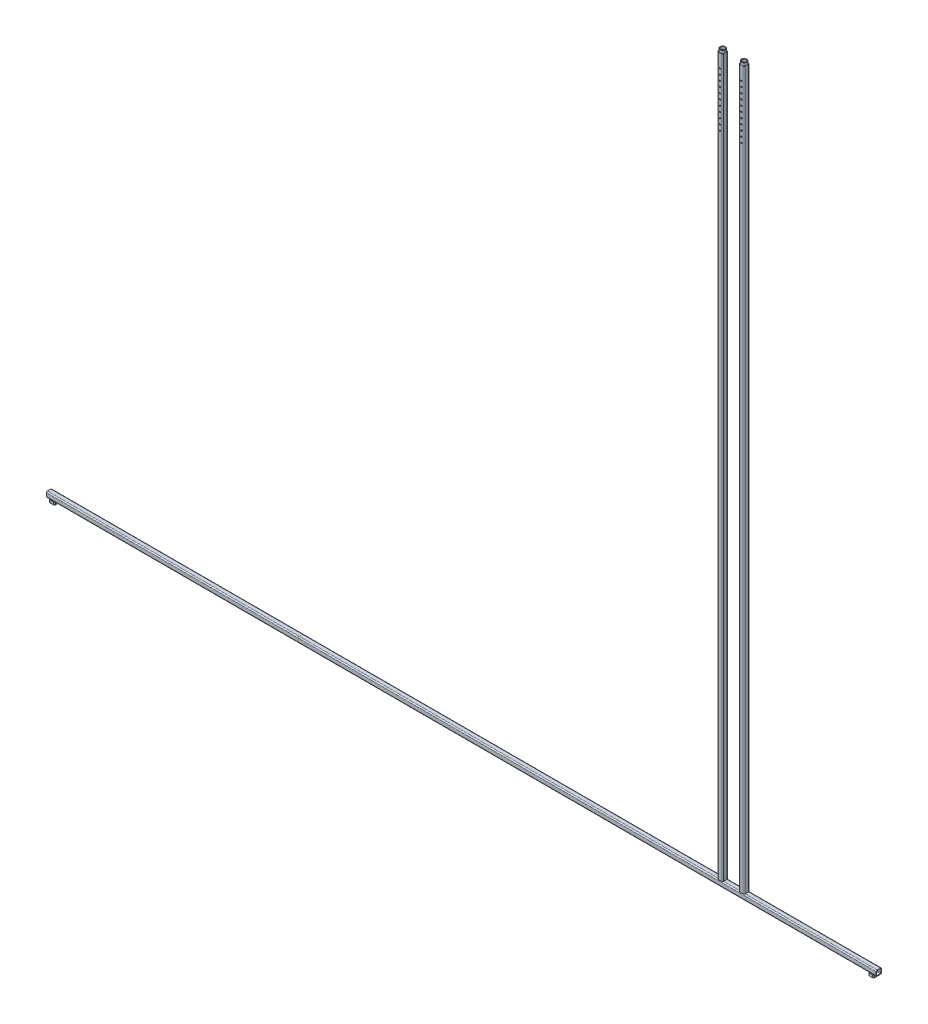
SolidWorks part; units mm, degrees
material "ASTM A36 Steel"
ref_plane "Front Plane" through (0, 0, 0) normal (0, 0, 1) x (1, 0, 0)
ref_plane "Top Plane" through (0, 0, 0) normal (0, 1, 0) x (1, 0, 0)
ref_plane "Right Plane" through (0, 0, 0) normal (1, 0, 0) x (0, 0, -1)
sketch "Sketch2" plane through (0, 0, 0) normal (0, 0, 1) x (1, 0, 0)
  line L0 (385.4461, 689.476) -> (385.4461, -1970.524)
  line L1 (305.4461, 689.476) -> (305.4461, -1970.524)
  line L2 (-2174.5539, -1990.524) -> (-2174.5539, -2000.524)
  line L3 (865.4461, -1990.524) -> (865.4461, -2000.524)
  line L4 (-1260.5539, -1980.524) -> (-2194.5539, -1980.524)
  line L5 (-1260.5539, -1980.524) -> (885.4461, -1980.524)
  dimension "D1" = 2660
  dimension "D2" = 80
  dimension "D3" = 2500
  dimension "D4" = 20
  dimension "D5" = 20
  dimension "D6" = 500
other "Square tube 20 X 20 X 2(1)"
ref_plane "Plane2" through (385.4461, 689.476, 0) normal (0, -1, 0) x (1, 0, 0)
sketch "Sketch1" plane through (385.4461, 689.476, 0) normal (0, -1, 0) x (1, 0, 0)
  line L0 (-6, -8) -> (6, -8)
  line L1 (-8, -6) -> (-8, 6)
  line L2 (6, 8) -> (-6, 8)
  line L3 (8, 6) -> (8, -6)
  line L4 (-6, -10) -> (6, -10)
  line L5 (-10, -6) -> (-10, 6)
  line L6 (6, 10) -> (-6, 10)
  line L7 (10, 6) -> (10, -6)
  arc A0 (10, 6) -> (6, 10) centre (6, 6) ccw
  arc A1 (6, -10) -> (10, -6) centre (6, -6) ccw
  arc A2 (-10, -6) -> (-6, -10) centre (-6, -6) ccw
  arc A3 (-6, 10) -> (-10, 6) centre (-6, 6) ccw
  arc A4 (-6, 8) -> (-8, 6) centre (-6, 6) ccw
  arc A5 (8, 6) -> (6, 8) centre (6, 6) ccw
  arc A6 (6, -8) -> (8, -6) centre (6, -6) ccw
  arc A7 (-8, -6) -> (-6, -8) centre (-6, -6) ccw
  point P0 (-10, 0)
  point P1 (10, 0)
  point P2 (0, 10)
  point P3 (0, -10)
  point P4 (0, 0)
  point P5 (-10, -10)
  point P6 (10, -10)
  point P7 (10, 10)
  point P8 (-10, 10)
  point P33 (0, 0)
  dimension "D1" = 4
  dimension "Thickness" = 2
  dimension "V_leg" = 20
other "Square tube 20 X 20 X 2(2)"
ref_plane "Plane3" through (-1260.5539, -1980.524, 0) normal (-1, 0, 0) x (0, -1, 0)
sketch "Sketch11" plane through (-1260.5539, -1980.524, 0) normal (-1, 0, 0) x (0, -1, 0)
  line L0 (-6, -8) -> (6, -8)
  line L1 (-8, -6) -> (-8, 6)
  line L2 (6, 8) -> (-6, 8)
  line L3 (8, 6) -> (8, -6)
  line L4 (-6, -10) -> (6, -10)
  line L5 (-10, -6) -> (-10, 6)
  line L6 (6, 10) -> (-6, 10)
  line L7 (10, 6) -> (10, -6)
  arc A0 (10, 6) -> (6, 10) centre (6, 6) ccw
  arc A1 (6, -10) -> (10, -6) centre (6, -6) ccw
  arc A2 (-10, -6) -> (-6, -10) centre (-6, -6) ccw
  arc A3 (-6, 10) -> (-10, 6) centre (-6, 6) ccw
  arc A4 (-6, 8) -> (-8, 6) centre (-6, 6) ccw
  arc A5 (8, 6) -> (6, 8) centre (6, 6) ccw
  arc A6 (6, -8) -> (8, -6) centre (6, -6) ccw
  arc A7 (-8, -6) -> (-6, -8) centre (-6, -6) ccw
  point P0 (-10, 0)
  point P1 (10, 0)
  point P2 (0, 10)
  point P3 (0, -10)
  point P4 (0, 0)
  point P5 (-10, -10)
  point P6 (10, -10)
  point P7 (10, 10)
  point P8 (-10, 10)
  point P33 (0, 0)
  dimension "D1" = 4
  dimension "Thickness" = 2
  dimension "V_leg" = 20
other "Square tube 20 X 20 X 2(4)"
ref_plane "Plane5" through (-2174.5539, -1990.524, 0) normal (0, -1, 0) x (1, 0, 0)
sketch "Sketch13" plane through (-2174.5539, -1990.524, 0) normal (0, -1, 0) x (1, 0, 0)
  line L0 (-6, -8) -> (6, -8)
  line L1 (-8, -6) -> (-8, 6)
  line L2 (6, 8) -> (-6, 8)
  line L3 (8, 6) -> (8, -6)
  line L4 (-6, -10) -> (6, -10)
  line L5 (-10, -6) -> (-10, 6)
  line L6 (6, 10) -> (-6, 10)
  line L7 (10, 6) -> (10, -6)
  arc A0 (10, 6) -> (6, 10) centre (6, 6) ccw
  arc A1 (6, -10) -> (10, -6) centre (6, -6) ccw
  arc A2 (-10, -6) -> (-6, -10) centre (-6, -6) ccw
  arc A3 (-6, 10) -> (-10, 6) centre (-6, 6) ccw
  arc A4 (-6, 8) -> (-8, 6) centre (-6, 6) ccw
  arc A5 (8, 6) -> (6, 8) centre (6, 6) ccw
  arc A6 (6, -8) -> (8, -6) centre (6, -6) ccw
  arc A7 (-8, -6) -> (-6, -8) centre (-6, -6) ccw
  point P0 (-10, 0)
  point P1 (10, 0)
  point P2 (0, 10)
  point P3 (0, -10)
  point P4 (0, 0)
  point P5 (-10, -10)
  point P6 (10, -10)
  point P7 (10, 10)
  point P8 (-10, 10)
  point P33 (0, 0)
  dimension "D1" = 4
  dimension "Thickness" = 2
  dimension "V_leg" = 20
sketch "Sketch14" plane through (0, 0, -10) normal (0, 0, -1) x (-1, 0, 0)
  line L0 (-379.4461, 689.476) -> (-391.4461, 689.476) construction
  circle A0 centre (-384.8471, 639.476) radius 2.5
  dimension "D1" = 50
extrude "Cut-Extrude1" cut sketch "Sketch14" against normal through all both and the other way through all
pattern_linear "LPattern1" count 11 spacing 20 along (0, -1, 0) of "Cut-Extrude1"
sketch "Sketch15" plane through (0, 0, -10) normal (0, 0, -1) x (-1, 0, 0)
  line L0 (-299.4461, 689.476) -> (-311.4461, 689.476) construction
  circle A0 centre (-305.4461, 639.476) radius 2.5
  dimension "D1" = 50
extrude "Cut-Extrude2" cut sketch "Sketch15" against normal through all both and the other way through all
pattern_linear "LPattern2" count 11 spacing 20 along (0, -1, 0) of "Cut-Extrude2"
sketch "Sketch16" plane through (0, 689.476, 0) normal (0, 1, 0) x (1, 0, 0)
  circle A0 centre (385.4461, 0) radius 10
  circle A1 centre (385.4461, 0) radius 8
extrude "Boss-Extrude1" add sketch "Sketch16" along normal blind 10 separate body
sketch "Sketch18" plane through (0, 689.476, 0) normal (0, 1, 0) x (1, 0, 0)
  circle A0 centre (305.3878, 0.0158) radius 8.0158
  circle A1 centre (305.3878, 0.0158) radius 9.9419
extrude "Boss-Extrude2" add sketch "Sketch18" along normal blind 10 separate body
